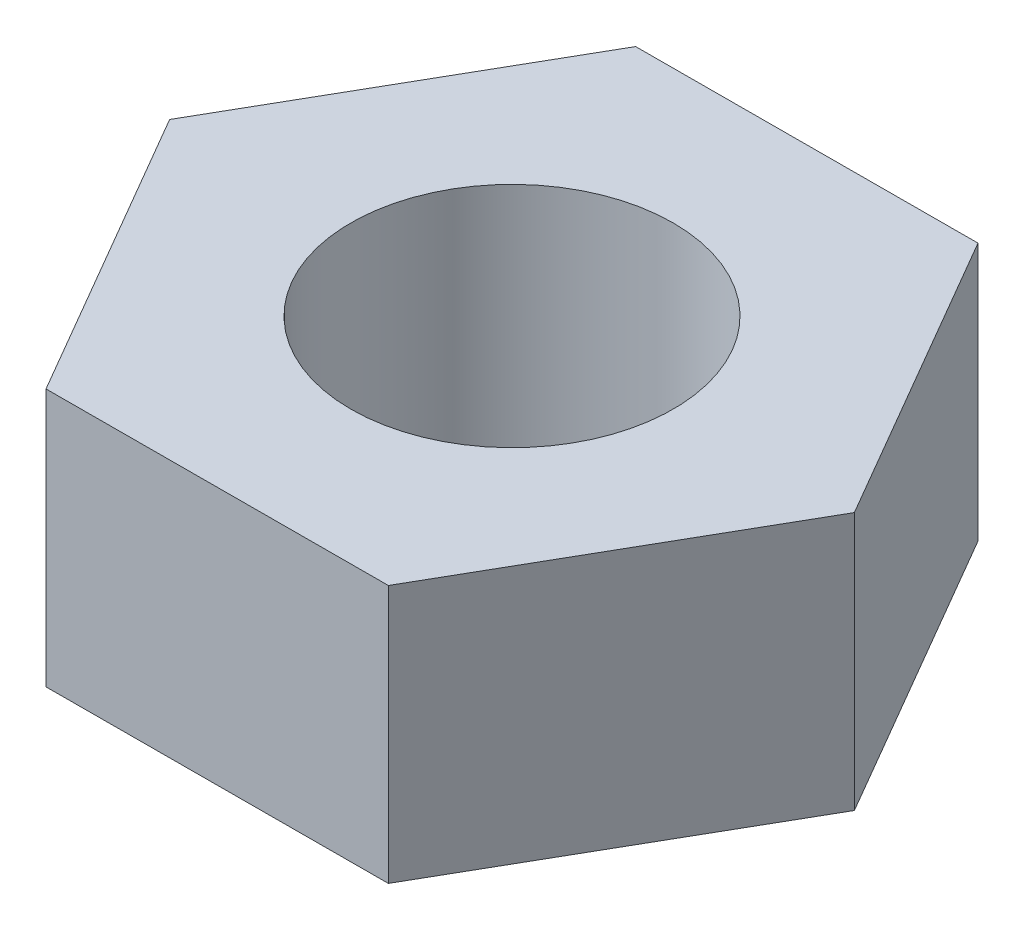
SolidWorks part; units mm, degrees
ref_plane "前视基准面" through (0, 0, 0) normal (0, 0, 1) x (1, 0, 0)
ref_plane "上视基准面" through (0, 0, 0) normal (0, 1, 0) x (1, 0, 0)
ref_plane "右视基准面" through (0, 0, 0) normal (1, 0, 0) x (0, 0, -1)
other "Configuration Table"
sketch "草图1" plane through (0, 0, 0) normal (0, 1, 0) x (1, 0, 0)
  line L1 (1.5955, -2.7455) -> (3.1754, 0.009)
  line L2 (3.1754, 0.009) -> (1.5799, 2.7545)
  line L3 (1.5799, 2.7545) -> (-1.5955, 2.7455)
  line L4 (-1.5955, 2.7455) -> (-3.1754, -0.009)
  line L5 (-3.1754, -0.009) -> (-1.5799, -2.7545)
  line L6 (-1.5799, -2.7545) -> (1.5955, -2.7455)
  circle A0 centre (0, 0) radius 2.75 construction
  circle A1 centre (0, 0) radius 1.5
  dimension "D2" = 3
  dimension "D1" = 5.5
extrude "凸台-拉伸1" add sketch "草图1" along normal blind 2.4
